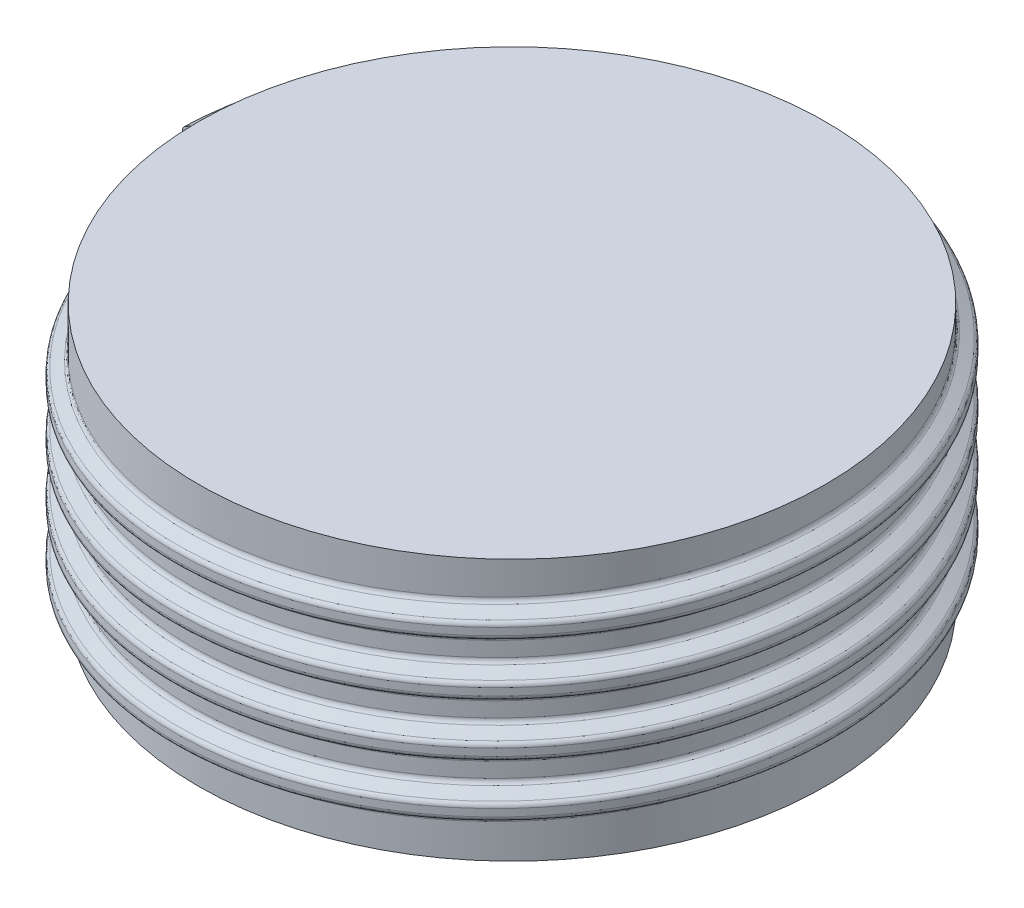
SolidWorks part; units mm, degrees
ref_plane "Front Plane" through (0, 0, 0) normal (0, 0, 1) x (1, 0, 0)
ref_plane "Top Plane" through (0, 0, 0) normal (0, 1, 0) x (1, 0, 0)
ref_plane "Right Plane" through (0, 0, 0) normal (1, 0, 0) x (0, 0, -1)
sketch "Sketch1" plane through (0, 0, 0) normal (0, 1, 0) x (1, 0, 0)
  circle A0 centre (0, 0) radius 30.48
  dimension "D1" = 60.96
extrude "Boss-Extrude1" add sketch "Sketch1" along normal blind 25.4 contours A0
thread "Thread1" pitch 5.08 profile "Thread Profile2" start angle 0, offset 0, length 20.32, pitch 5.08, diameter 60.96
ref_plane "Plane2" through (-30.48, 25.4, 0) normal (0, 0, 1) x (-1, 0, 0)
sketch "Thread Profile2" plane through (-30.48, 25.4, 0) normal (0, 0, 1) x (-1, 0, 0)
  line L0 (0, 0) -> (0, 5.08) construction
  line L1 (0, 0) -> (0, 3.6346)
  line L2 (0.508, 3.6346) -> (1.524, 3.6346) construction
  line L3 (1.524, 2.1681) -> (1.524, 1.4665)
  line L4 (1.27, 2.6081) -> (0.254, 3.1946)
  line L5 (1.27, 1.0265) -> (0.254, 0.4399)
  line L6 (0.508, 0) -> (1.524, 0) construction
  arc A0 (0.254, 3.1946) -> (0, 3.6346) centre (0.508, 3.6346) cw
  arc A1 (0.254, 0.4399) -> (0, 0) centre (0.508, 0) ccw
  arc A2 (1.524, 1.4665) -> (1.27, 1.0265) centre (1.016, 1.4665) cw
  arc A3 (1.524, 2.1681) -> (1.27, 2.6081) centre (1.016, 2.1681) ccw
  point P10 (1.524, 2.4614)
  point P17 (1.524, 1.1732)
  point P18 (0, 3.3413)
  point P19 (0, 0.2933)
  point P20 (0, 0)
  dimension "RootFillet1" = 0.508
  dimension "RootFillet2" = 0.508
  dimension "CrestFillet2" = 0.508
  dimension "CrestFillet1" = 0.508
  dimension "Pitch" = 5.08
  dimension "Angle1" = 30
  dimension "Angle2" = 30
  dimension "a" = 3.048
  dimension "b" = 1.524
  dimension "c" = 1.2882
